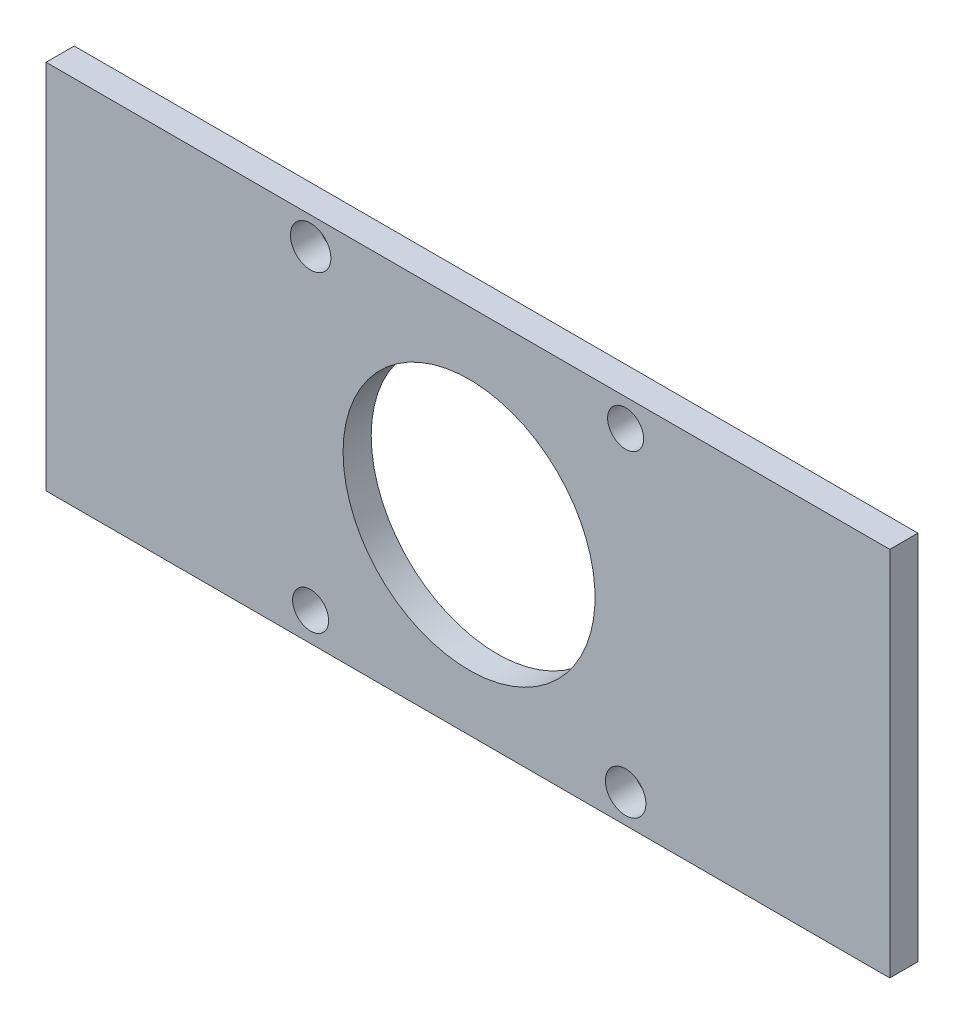
SolidWorks part; units mm, degrees
ref_plane "Front Plane" through (0, 0, 0) normal (0, 0, 1) x (1, 0, 0)
ref_plane "Top Plane" through (0, 0, 0) normal (0, 1, 0) x (1, 0, 0)
ref_plane "Right Plane" through (0, 0, 0) normal (1, 0, 0) x (0, 0, -1)
sketch "Sketch1" plane through (0, 0, 0) normal (0, 0, 1) x (1, 0, 0)
  line L1 (-50.165, -23.622) -> (45.085, -23.622)
  line L2 (-50.165, -23.622) -> (-50.165, 18.288)
  line L3 (-50.165, 18.288) -> (45.085, 18.288)
  line L4 (45.085, -23.622) -> (45.085, 18.288)
  point P0 (0, 0)
  point P6 (0, 0)
  dimension "D1" = 95.25
  dimension "D2" = 41.91
extrude "Boss-Extrude1" add sketch "Sketch1" along normal mid plane 3.175
sketch "Sketch2" plane through (0, 0, -1.5875) normal (0, 0, -1) x (-1, 0, 0)
  line L1 (50.165, 18.288) -> (50.165, -23.622) construction
  line L2 (-15.2601, 15.1954) -> (20.2999, 15.1954) construction
  line L3 (-15.2601, 15.1954) -> (-15.2601, -20.3646) construction
  line L4 (-15.2601, -20.3646) -> (20.2999, -20.3646) construction
  line L5 (20.2999, 15.1954) -> (20.2999, -20.3646) construction
  line L6 (50.165, -23.622) -> (-45.085, -23.622) construction
  circle A0 centre (2.413, -3.048) radius 14.224
  circle A1 centre (-15.2601, -20.3646) radius 2.286
  circle A2 centre (-15.2601, 15.1954) radius 2.032
  circle A3 centre (20.2999, 15.1954) radius 2.286
  circle A4 centre (20.2999, -20.3646) radius 2.032
  dimension "D1" = 28.448
  dimension "D2" = 4.572
  dimension "D3" = 4.064
  dimension "D4" = 20.574
  dimension "D5" = 47.752
  dimension "D6" = 35.56
  dimension "D7" = 35.56
  dimension "D8" = 25.4
extrude "Cut-Extrude1" cut sketch "Sketch2" against normal blind 3.175 contours A0 | A1 | A2 | A3 | A4
